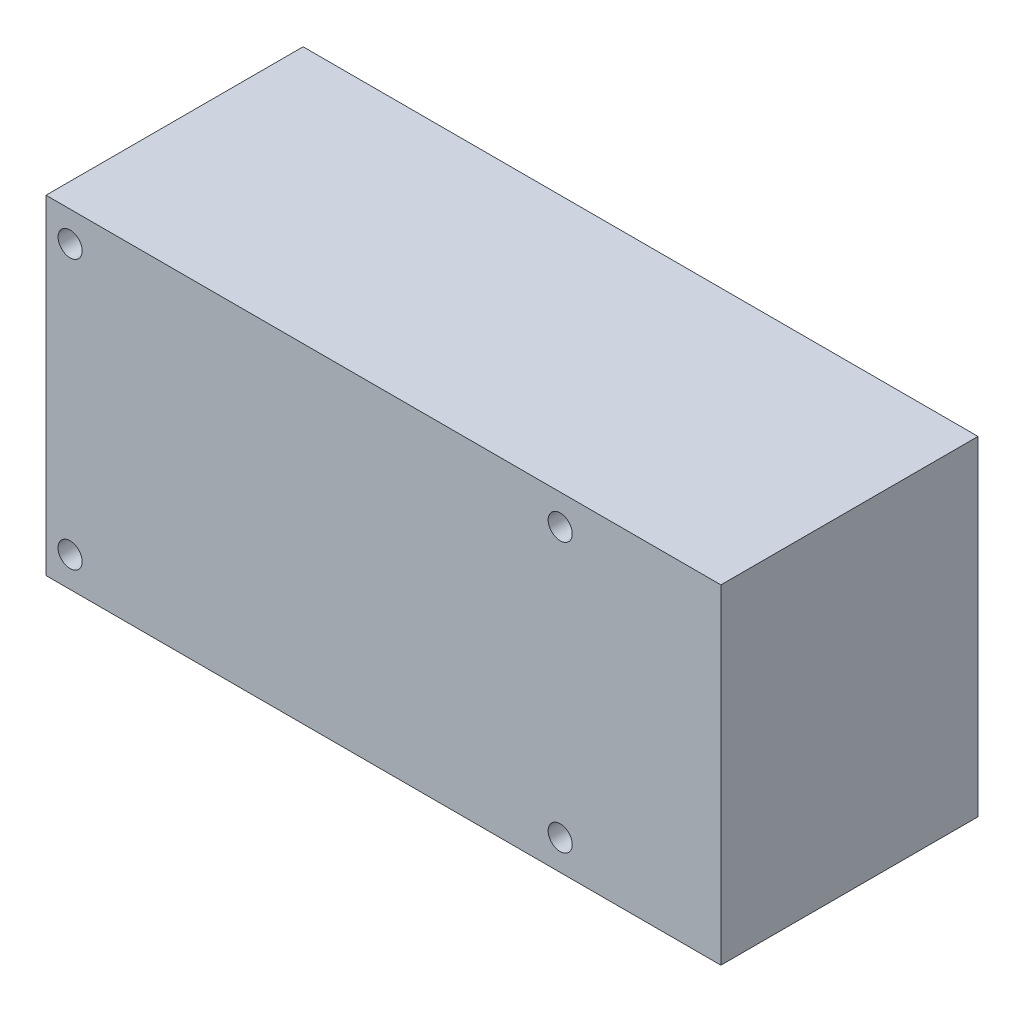
SolidWorks part; units mm, degrees
ref_plane "前视基准面" through (0, 0, 0) normal (0, 0, 1) x (1, 0, 0)
ref_plane "上视基准面" through (0, 0, 0) normal (0, 1, 0) x (1, 0, 0)
ref_plane "右视基准面" through (0, 0, 0) normal (1, 0, 0) x (0, 0, -1)
sketch "草图1" plane through (0, 0, 0) normal (0, 0, 1) x (1, 0, 0)
  line L1 (0, 0) -> (84, 0)
  line L2 (0, 0) -> (0, 41)
  line L3 (0, 41) -> (84, 41)
  line L4 (84, 0) -> (84, 41)
  dimension "D1" = 84
  dimension "D2" = 41
extrude "凸台-拉伸1" add sketch "草图1" along normal blind 32
sketch "草图2" plane through (0, 0, 32) normal (0, 0, 1) x (1, 0, 0)
  line L0 (0, 20.5) -> (84, 20.5) construction
  line L1 (0, 41) -> (0, 0) construction
  line L2 (84, 0) -> (84, 41) construction
  circle A0 centre (3, 3.75) radius 1.5
  circle A1 centre (64, 3.75) radius 1.5
  circle A2 centre (64, 37.25) radius 1.5
  circle A3 centre (3, 37.25) radius 1.5
  dimension "D1" = 3
  dimension "D2" = 33.5
  dimension "D4" = 3
  dimension "D3" = 3
  dimension "D5" = 61
extrude "切除-拉伸1" cut sketch "草图2" against normal blind 32
